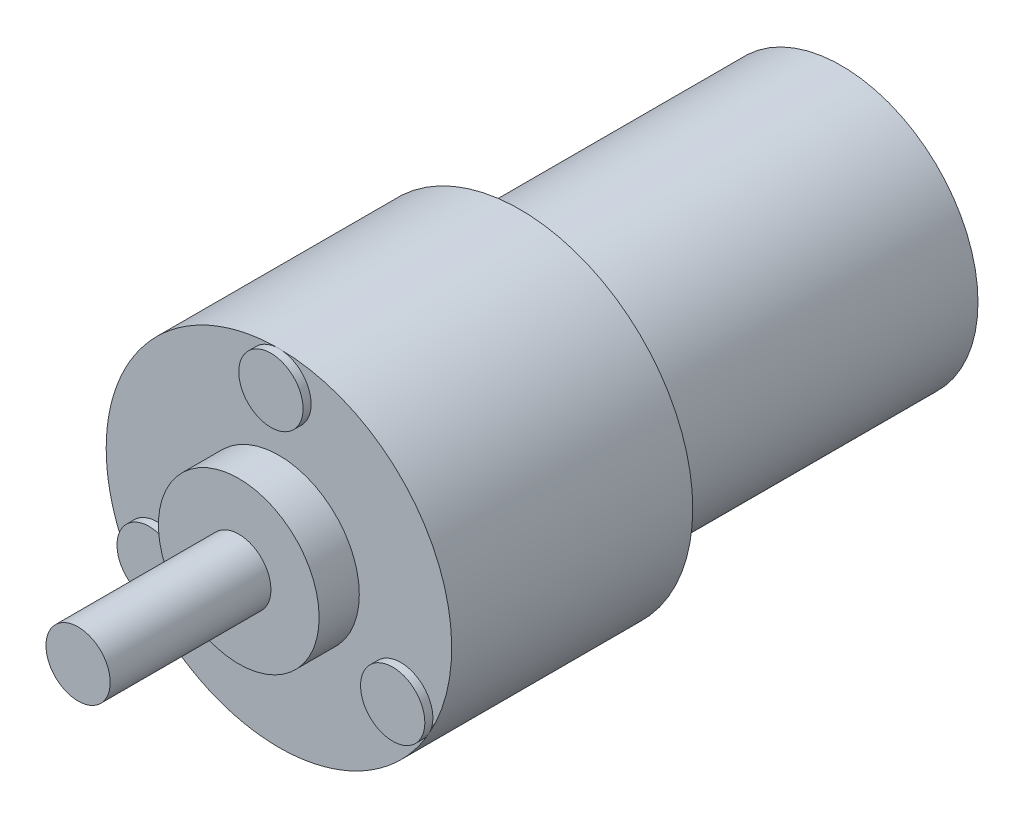
SolidWorks part; units mm, degrees
ref_plane "Plan de face" through (0, 0, 0) normal (0, 0, 1) x (1, 0, 0)
ref_plane "Plan de dessus" through (0, 0, 0) normal (0, 1, 0) x (1, 0, 0)
ref_plane "Plan de droite" through (0, 0, 0) normal (1, 0, 0) x (0, 0, -1)
sketch "Esquisse1" plane through (0, 0, 0) normal (0, 0, 1) x (1, 0, 0)
  circle A0 centre (0, 0) radius 21.5
  dimension "D1" = 43
extrude "Extrusion1" add sketch "Esquisse1" along normal blind 30
sketch "Esquisse2" plane through (0, 0, 30) normal (0, 0, 1) x (1, 0, 0)
  circle A0 centre (0, 0) radius 10
  dimension "D1" = 20
extrude "Extrusion2" add sketch "Esquisse2" along normal blind 5
sketch "Esquisse3" plane through (0, 0, 35) normal (0, 0, 1) x (1, 0, 0)
  circle A0 centre (0, 0) radius 4
  dimension "D1" = 8
extrude "Extrusion3" add sketch "Esquisse3" along normal blind 20
sketch "Esquisse4" plane through (0, 0, 0) normal (0, 0, -1) x (-1, 0, 0)
  circle A0 centre (0, 0) radius 17
  dimension "D1" = 34
extrude "Extrusion4" add sketch "Esquisse4" along normal blind 40
sketch "Esquisse5" plane through (0, 0, 30) normal (0, 0, 1) x (1, 0, 0)
  line L0 (0, 17.5) -> (0, 0) construction
  line L1 (0, 0) -> (-15.1554, -8.75) construction
  line L2 (0, 0) -> (15.1554, -8.75) construction
  circle A0 centre (0, 17.5) radius 4
  circle A2 centre (0, 0) radius 21.5 construction
  circle A3 centre (-15.1554, -8.75) radius 4
  circle A4 centre (15.1554, -8.75) radius 4
  dimension "D1" = 8
  dimension "D2" = 8
  dimension "D3" = 8
  dimension "D4" = 120
  dimension "D5" = 120
extrude "Extrusion5" add sketch "Esquisse5" along normal blind 1
